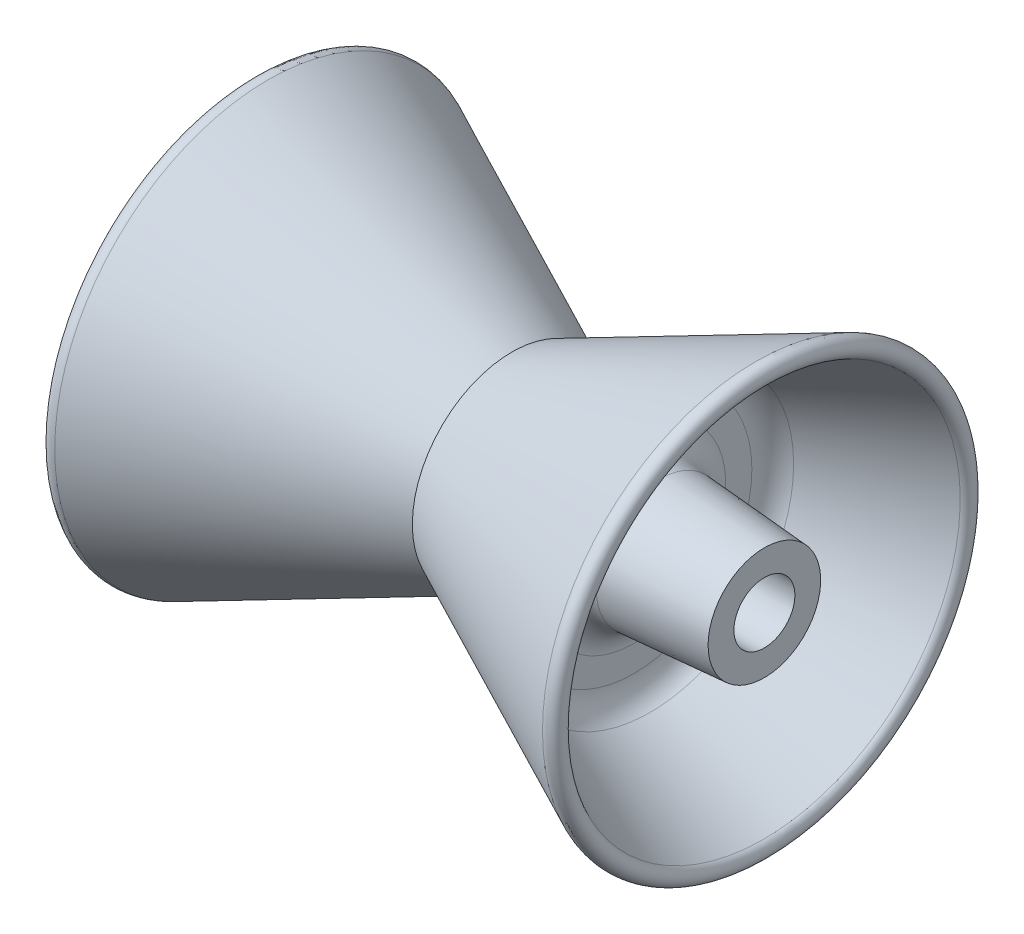
SolidWorks part; units mm, degrees
ref_plane "Front Plane" through (0, 0, 0) normal (0, 0, 1) x (1, 0, 0)
ref_plane "Top Plane" through (0, 0, 0) normal (0, 1, 0) x (1, 0, 0)
ref_plane "Right Plane" through (0, 0, 0) normal (1, 0, 0) x (0, 0, -1)
sketch "Sketch1" plane through (0, 0, 0) normal (0, 0, 1) x (1, 0, 0)
  line L0 (0, 0) -> (13665.962, 0) construction
  line L1 (13665.962, 825.5) -> (13665.962, 1524)
  line L2 (5019.3677, 3036.2594) -> (6832.981, 2190.5577)
  line L3 (10134.981, 825.5) -> (9626.981, 825.5)
  line L4 (10134.981, 825.5) -> (13665.962, 825.5)
  line L6 (13435.7598, 5777.484) -> (6832.981, 2698.5577)
  line L7 (13650.4499, 5317.0796) -> (10574.9459, 3882.9486)
  line L8 (10134.981, 2487.1547) -> (10134.981, 3192.342)
  line L9 (10842.308, 1727.1187) -> (13665.962, 1524)
  line L10 (9626.981, 2411.6842) -> (9626.981, 825.5)
  line L11 (8646.5943, 3036.2594) -> (6832.981, 2190.5577)
  line L12 (4038.981, 2411.6842) -> (4038.981, 825.5)
  line L13 (2823.654, 1727.1187) -> (0, 1524)
  line L14 (3530.981, 2487.1547) -> (3530.981, 3192.342)
  line L15 (15.5121, 5317.0796) -> (3091.0161, 3882.9486)
  line L16 (230.2022, 5777.484) -> (6832.981, 2698.5577)
  line L17 (3530.981, 825.5) -> (0, 825.5)
  line L18 (3530.981, 825.5) -> (4038.981, 825.5)
  line L19 (0, 825.5) -> (0, 1524)
  arc A0 (13650.4499, 5317.0796) -> (13435.7598, 5777.484) centre (13543.1049, 5547.2818) ccw
  arc A1 (10574.9459, 3882.9486) -> (10134.981, 3192.342) centre (10896.981, 3192.342) ccw
  arc A2 (10134.981, 2487.1547) -> (10842.308, 1727.1187) centre (10896.981, 2487.1547) ccw
  arc A3 (9626.981, 2411.6842) -> (8646.5943, 3036.2594) centre (8937.8385, 2411.6842) ccw
  arc A4 (4038.981, 2411.6842) -> (5019.3677, 3036.2594) centre (4728.1235, 2411.6842) cw
  arc A5 (3530.981, 2487.1547) -> (2823.654, 1727.1187) centre (2768.981, 2487.1547) cw
  arc A6 (3091.0161, 3882.9486) -> (3530.981, 3192.342) centre (2768.981, 3192.342) cw
  arc A7 (15.5121, 5317.0796) -> (230.2022, 5777.484) centre (122.8571, 5547.2818) cw
  dimension "D7" = 4107.6796
  dimension "D6" = 1524
  dimension "D9" = 254
  dimension "D10" = 689.1425
  dimension "D3" = 5777.484
  dimension "D4" = 825.5
  dimension "D5" = 1524
  dimension "D8" = 705.1873
revolve "Revolve2" add sketch "Sketch1" angle 360 about L0
